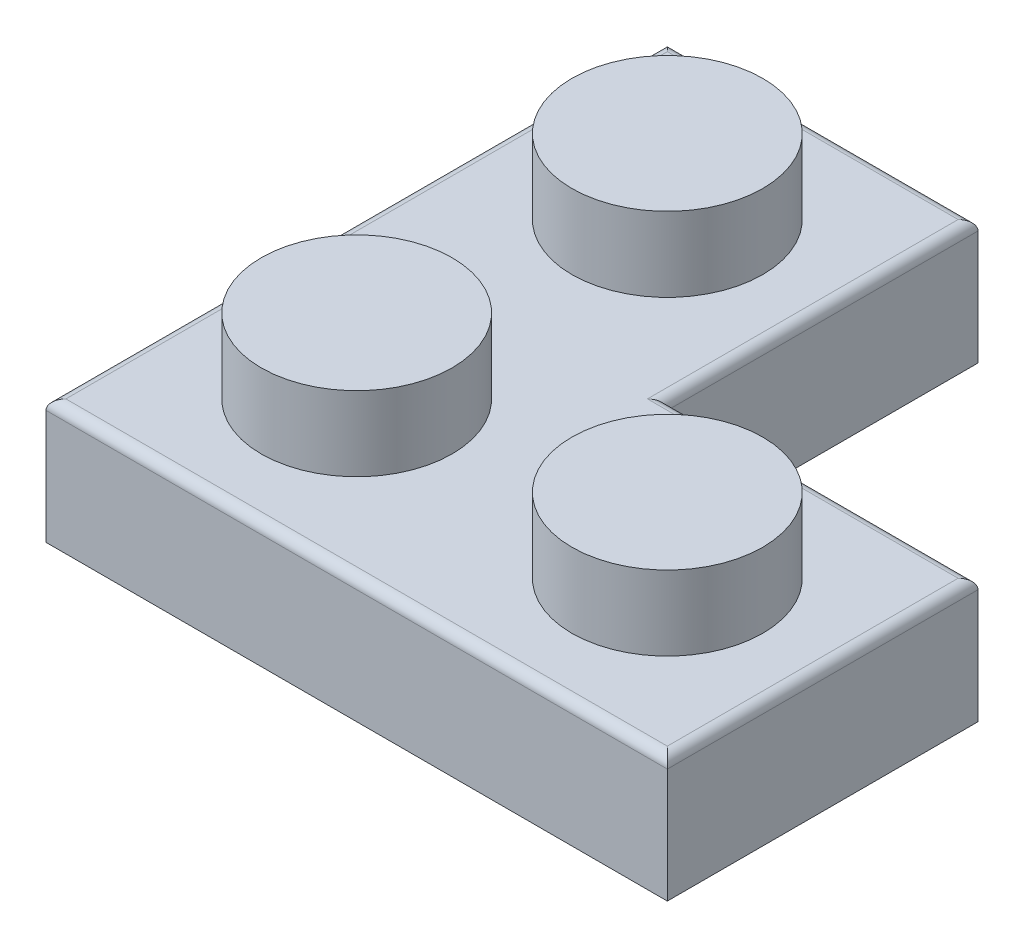
SolidWorks part; units mm, degrees
ref_plane "Front" through (0, 0, 0) normal (0, 0, 1) x (1, 0, 0)
ref_plane "Top" through (0, 0, 0) normal (0, 1, 0) x (1, 0, 0)
ref_plane "Right" through (0, 0, 0) normal (1, 0, 0) x (0, 0, -1)
sketch "Sketch1" plane through (0, 0, 0) normal (0, 1, 0) x (1, 0, 0)
  line L0 (0, 0) -> (0, 50.4571) construction
  line L1 (0, 0) -> (55.8847, 0) construction
  line L2 (-7.9375, 7.9375) -> (7.9375, 7.9375)
  line L3 (-7.9375, 7.9375) -> (-7.9375, -7.9375)
  line L4 (7.9375, -7.9375) -> (-7.9375, -7.9375)
  line L5 (7.9375, -7.9375) -> (7.9375, 7.9375)
  dimension "Length" = 15.875
  dimension "Width" = 15.875
extrude "Base-Extrude" add sketch "Sketch1" along normal blind 3.175
sketch "Sketch2" plane through (0, 3.175, 0) normal (0, 1, 0) x (-1, 0, 0)
  line L0 (7.9375, -7.9375) -> (7.9375, 7.9375) construction
  line L1 (-7.9375, 7.9375) -> (7.9375, 7.9375) construction
  circle A0 centre (3.9688, 3.9687) radius 2.4384
  dimension "DotDiam" = 4.8768
  dimension "DotLSpc" = 3.9688
  dimension "DotWSpc" = 3.9688
extrude "Boss-Extrude1" add sketch "Sketch2" along normal blind 1.905
pattern_linear "LPattern4" count 2 spacing 7.9375 along (1, 0, 0) count 2 spacing 7.9375 along (0, 0, -1) of "Boss-Extrude1"
sketch "Sketch3" plane through (0, 3.175, 0) normal (0, 1, 0) x (-1, 0, 0)
  line L0 (0, -7.9375) -> (0, 0)
  line L1 (7.9375, -7.9375) -> (-7.9375, -7.9375) construction
  line L2 (0, 0) -> (-7.9375, 0)
  line L3 (-7.9375, 7.9375) -> (-7.9375, -7.9375) construction
extrude "Cut-Extrude1" cut sketch "Sketch3" against normal through all and the other way blind 7.9375
shell "Shell1" thickness 1.5875
sketch "Sketch4" plane through (0, 1.5875, 0) normal (0, -1, 0) x (1, 0, 0)
  circle A0 centre (-3.81, 0) radius 1.27
  circle A1 centre (0, 3.81) radius 1.27
  dimension "D1" = 2.54
extrude "Boss-Extrude2" add sketch "Sketch4" along normal up to surface (1.5875 mm away)
sketch "Sketch5" plane through (0, 0, 0) normal (0, -1, 0) x (1, 0, 0)
  circle A0 centre (0, 3.81) radius 0.635
  circle A1 centre (-3.81, 0) radius 0.635
  dimension "D1" = 1.27
extrude "Cut-Extrude2" cut sketch "Sketch5" against normal up to surface (1.5875 mm away)
fillet "Fillet1" radius 0.254 6 edges at (7.9375, 3.175, 3.9687) (-3.9688, 3.175, -7.9375) (0, 3.175, -3.9687) (3.9688, 3.175, 0) (-7.9375, 3.175, 0) (0, 3.175, 7.9375)
